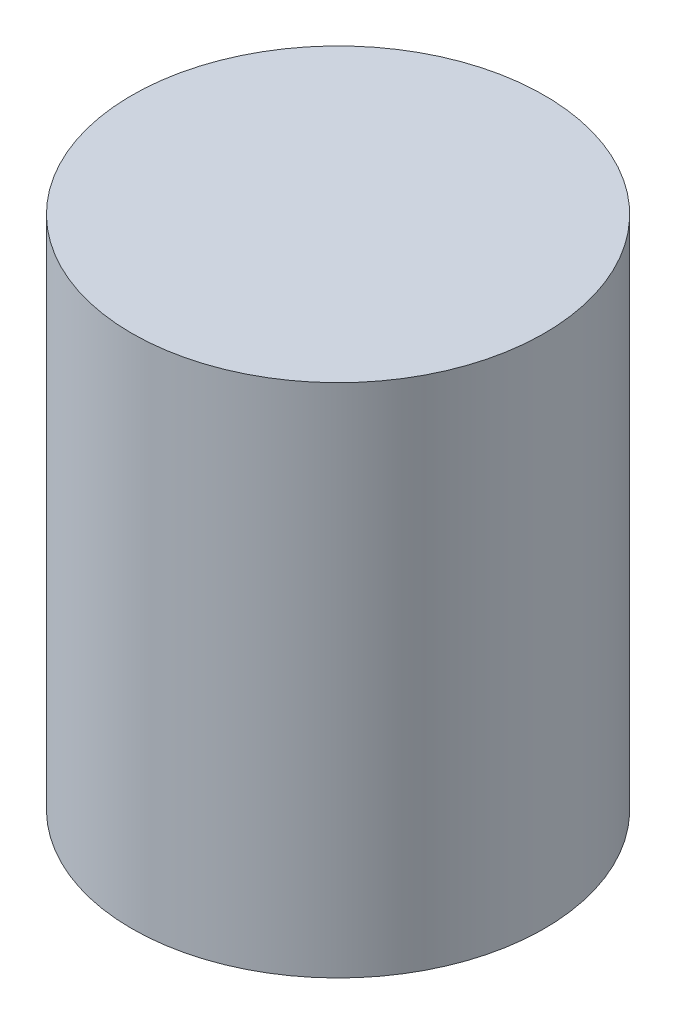
SolidWorks part; units mm, degrees
ref_plane "Front Plane" through (0, 0, 0) normal (0, 0, 1) x (1, 0, 0)
ref_plane "Top Plane" through (0, 0, 0) normal (0, 1, 0) x (1, 0, 0)
ref_plane "Right Plane" through (0, 0, 0) normal (1, 0, 0) x (0, 0, -1)
sketch "Sketch1" plane through (0, 0, 0) normal (0, 1, 0) x (1, 0, 0)
  circle A0 centre (0, 0) radius 40
  dimension "D1" = 80
extrude "Boss-Extrude1" add sketch "Sketch1" along normal blind 100
